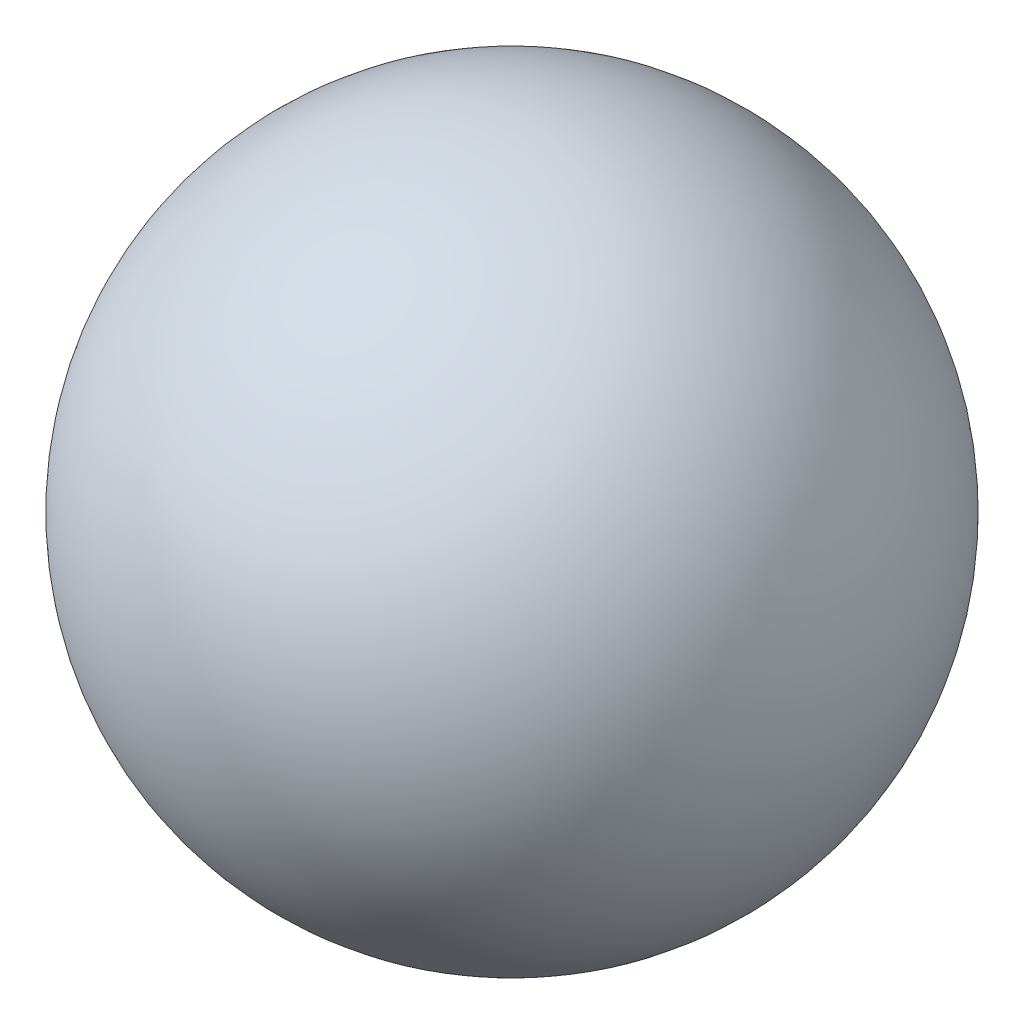
SolidWorks part; units mm, degrees
ref_plane "Front" through (0, 0, 0) normal (0, 0, 1) x (1, 0, 0)
ref_plane "Top" through (0, 0, 0) normal (0, 1, 0) x (1, 0, 0)
ref_plane "Right" through (0, 0, 0) normal (1, 0, 0) x (0, 0, -1)
sketch "Sketch1" plane through (0, 0, 0) normal (0, 0, 1) x (1, 0, 0)
  line L0 (0, -4) -> (0, 4)
  arc A0 (0, -4) -> (0, 4) centre (0, 0) ccw
  point P4 (0, 0)
  point P6 (0, 0)
  dimension "D1" = 8
revolve "Revolve1" add sketch "Sketch1" angle 360 about L0
